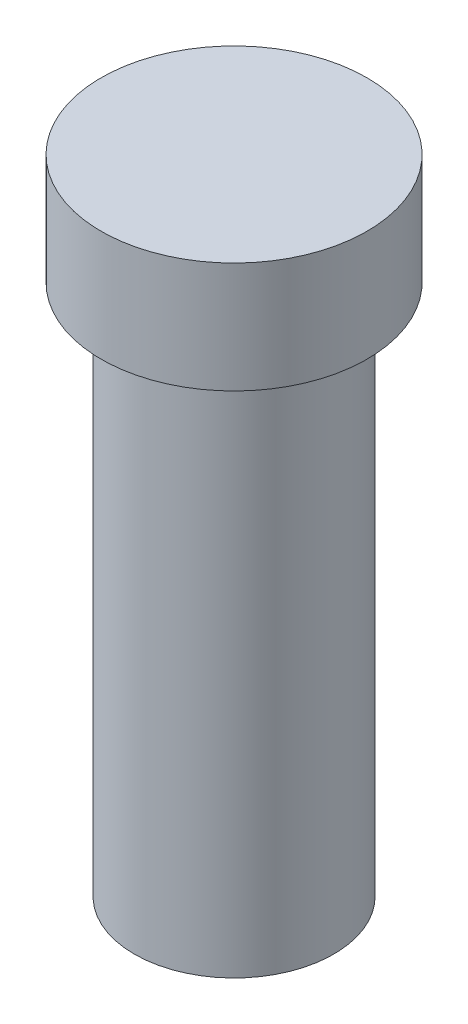
SolidWorks part; units mm, degrees
ref_plane "Front Plane" through (0, 0, 0) normal (0, 0, 1) x (1, 0, 0)
ref_plane "Top Plane" through (0, 0, 0) normal (0, 1, 0) x (1, 0, 0)
ref_plane "Right Plane" through (0, 0, 0) normal (1, 0, 0) x (0, 0, -1)
sketch "Sketch3" plane through (0, 0, 0) normal (0, 0, 1) x (1, 0, 0)
  line L0 (0, 0) -> (0, 368.3)
  line L1 (0, 368.3) -> (76.2, 368.3)
  line L2 (76.2, 368.3) -> (76.2, 304.8)
  line L3 (76.2, 304.8) -> (57.15, 304.8)
  line L4 (57.15, 304.8) -> (57.15, 0)
  line L5 (57.15, 0) -> (0, 0)
  point P7 (192.4297, 304.8)
  dimension "D1" = 368.3
  dimension "D2" = 63.5
  dimension "D3" = 76.2
  dimension "D4" = 57.15
revolve "Revolve1" add sketch "Sketch3" angle 360 about L0
